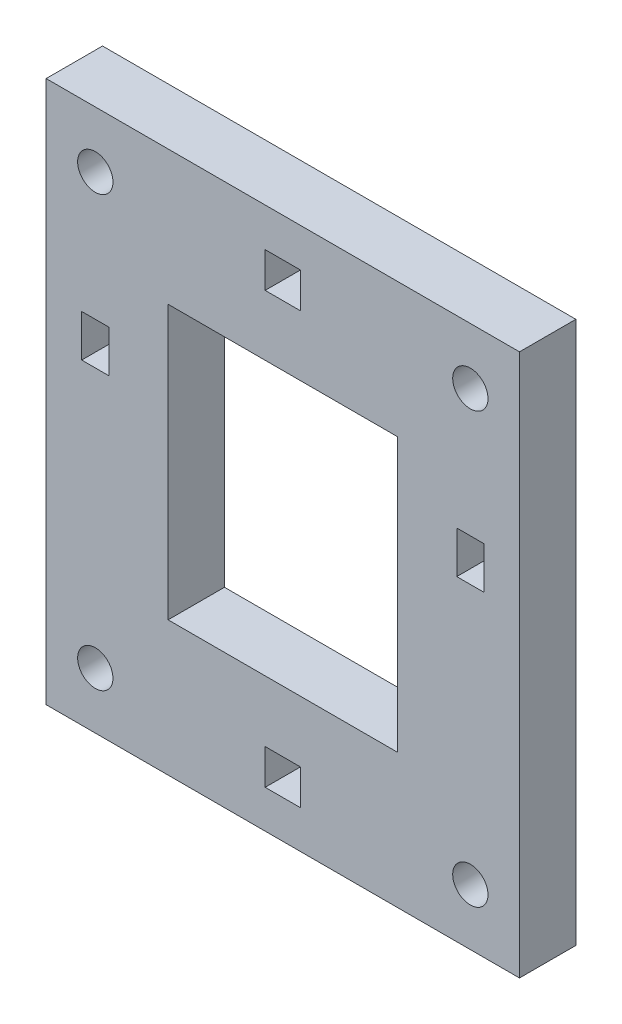
SolidWorks part; units mm, degrees
ref_plane "Спереди" through (0, 0, 0) normal (0, 0, 1) x (1, 0, 0)
ref_plane "Сверху" through (0, 0, 0) normal (0, 1, 0) x (1, 0, 0)
ref_plane "Справа" through (0, 0, 0) normal (1, 0, 0) x (0, 0, -1)
other "Configuration Table"
sketch "Эскиз1" plane through (0, 0, 0) normal (0, 0, 1) x (1, 0, 0)
  line L0 (-27.6979, 31.634) -> (-27.6979, -31.634) construction
  line L1 (-34.935, 39.925) -> (34.765, 39.925)
  line L2 (-34.935, 39.925) -> (-34.935, -39.925)
  line L3 (-34.935, -39.925) -> (34.765, -39.925)
  line L4 (34.765, 39.925) -> (34.765, -39.925)
  line L5 (-34.935, 39.925) -> (34.765, -39.925) construction
  line L6 (-34.935, -39.925) -> (34.765, 39.925) construction
  line L7 (-16.975, 20.12) -> (16.805, 20.12)
  line L8 (-16.975, 20.12) -> (-16.975, -20.12)
  line L9 (-16.975, -20.12) -> (16.805, -20.12)
  line L10 (16.805, 20.12) -> (16.805, -20.12)
  line L11 (-16.975, 20.12) -> (16.805, -20.12) construction
  line L12 (-16.975, -20.12) -> (16.805, 20.12) construction
  line L13 (27.5279, -31.634) -> (-27.6979, -31.634) construction
  line L14 (-27.6979, -31.634) -> (27.5279, -31.634) construction
  line L16 (27.5279, 31.634) -> (27.3735, 32.3839) construction
  line L17 (-27.6979, 31.634) -> (27.5279, 31.634) construction
  line L18 (-34.935, 0) -> (34.765, 0) construction
  line L19 (-0.085, 39.925) -> (-0.085, -39.925) construction
  line L21 (-29.6979, 12.844) -> (-25.6979, 12.844)
  line L22 (-29.6979, 12.844) -> (-29.6979, 6.644)
  line L23 (-29.6979, 6.644) -> (-25.6979, 6.644)
  line L24 (-25.6979, 12.844) -> (-25.6979, 6.644)
  line L25 (-29.6979, 12.844) -> (-25.6979, 6.644) construction
  line L26 (-29.6979, 6.644) -> (-25.6979, 12.844) construction
  line L30 (29.5279, 6.644) -> (25.5279, 6.644)
  line L31 (29.5279, 12.844) -> (25.5279, 12.844)
  line L32 (29.5279, 12.844) -> (29.5279, 6.644)
  line L33 (25.5279, 12.844) -> (25.5279, 6.644)
  circle A0 centre (-27.6979, 31.634) radius 2.6
  circle A1 centre (-27.6979, -31.634) radius 2.6
  circle A2 centre (27.5279, -31.634) radius 2.6
  circle A3 centre (27.5279, 31.634) radius 2.6
  point P0 (-0.085, 0)
  point P5 (27.5279, 29.034)
  point P6 (-0.085, 0)
  point P24 (-27.6979, 0)
  point P32 (-27.6979, 29.034)
  dimension "D5" = 5.2
  dimension "D6" = 5.2
  dimension "D7" = 5.2
  dimension "D8" = 5.2
  dimension "D1" = 79.85
  dimension "D2" = 69.7
  dimension "D3" = 40.24
  dimension "D4" = 33.78
  dimension "D9" = 6.2
  dimension "D10" = 4
  dimension "D11" = 16.19
extrude "Бобышка-Вытянуть1" add sketch "Эскиз1" along normal blind 8.3
sketch "Эскиз2" plane through (0, 0, 8.3) normal (0, 0, 1) x (1, 0, 0)
sketch "Эскиз3" plane through (0, 0, 8.3) normal (0, 0, 1) x (1, 0, 0)
  line L0 (-34.935, 39.925) -> (34.765, -39.925) construction
  line L1 (34.765, 39.925) -> (-34.935, -39.925) construction
  line L2 (-0.085, 39.925) -> (-0.085, -39.925) construction
  line L3 (34.765, 39.925) -> (-34.935, 39.925) construction
  line L4 (-34.935, -39.925) -> (34.765, -39.925) construction
  line L5 (-27.785, -31.7338) -> (-27.8176, -31.7711) construction
  line L6 (-27.8176, -31.7711) -> (27.5279, -31.634) construction
  line L8 (2.515, -29.1338) -> (-2.685, -29.1338)
  line L9 (2.515, -29.1338) -> (2.515, -34.3338)
  line L10 (2.515, -34.3338) -> (-2.685, -34.3338)
  line L11 (-2.685, -29.1338) -> (-2.685, -34.3338)
  line L12 (2.515, -29.1338) -> (-2.685, -34.3338) construction
  line L13 (2.515, -34.3338) -> (-2.685, -29.1338) construction
  point P17 (-0.085, -31.7338)
  point P24 (0, 0)
  dimension "D1" = 5.2
  dimension "D2" = 5.2
extrude "Вырез-Вытянуть1" cut sketch "Эскиз3" against normal blind 10
sketch "Эскиз5" plane through (0, 0, 8.3) normal (0, 0, 1) x (1, 0, 0)
  line L0 (-27.6979, 31.634) -> (27.5279, 31.634) construction
  line L1 (0, 0) -> (-0.085, 31.634) construction
  line L3 (-2.685, 34.234) -> (2.515, 34.234)
  line L4 (-2.685, 34.234) -> (-2.685, 29.034)
  line L5 (-2.685, 29.034) -> (2.515, 29.034)
  line L6 (2.515, 34.234) -> (2.515, 29.034)
  line L7 (-2.685, 34.234) -> (2.515, 29.034) construction
  line L8 (-2.685, 29.034) -> (2.515, 34.234) construction
  point P11 (0, 0)
  point P12 (0, 0)
  dimension "D1" = 5.2
  dimension "D2" = 5.2
extrude "Вырез-Вытянуть2" cut sketch "Эскиз5" against normal blind 10
